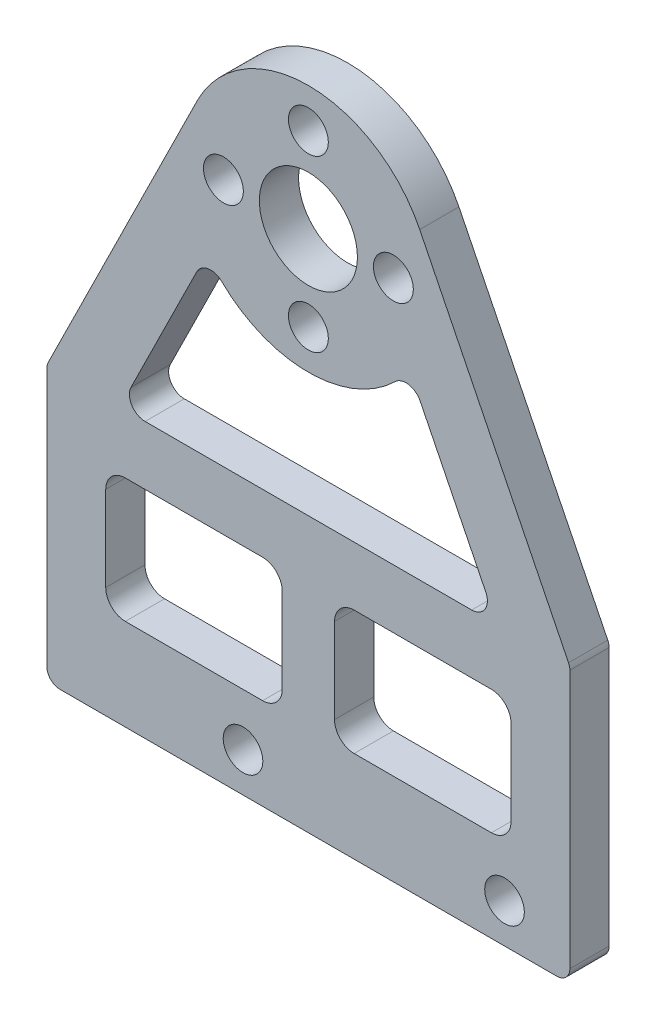
SolidWorks part; units mm, degrees
material "Thornel Mat VMA"
ref_plane "前视基准面" through (0, 0, 0) normal (0, 0, 1) x (1, 0, 0)
ref_plane "上视基准面" through (0, 0, 0) normal (0, 1, 0) x (1, 0, 0)
ref_plane "右视基准面" through (0, 0, 0) normal (1, 0, 0) x (0, 0, -1)
sketch "草图1" plane through (0, 0, 0) normal (0, 0, 1) x (1, 0, 0)
  line L0 (0, 0) -> (0, -40) construction
  line L1 (-20, -40) -> (20, -40)
  line L2 (20, -40) -> (20, -19)
  line L3 (20, -19) -> (8.5148, 4.2129)
  line L4 (-20, -19) -> (-8.5148, 4.2129)
  line L5 (-20, -40) -> (-20, -19)
  circle A0 centre (0, 0) radius 6.5 construction
  circle A1 centre (0, 6.5) radius 1.525
  circle A2 centre (6.5, 0) radius 1.525
  circle A3 centre (0, -6.5) radius 1.525
  circle A4 centre (-6.5, 0) radius 1.525
  circle A5 centre (0, 0) radius 3.75
  arc A6 (8.5148, 4.2129) -> (-8.5148, 4.2129) centre (0, 0) ccw
  point P14 (0, 0)
  point P18 (0, -40)
  dimension "D1" = 13
  dimension "D2" = 3.05
  dimension "D4" = 7.5
  dimension "D5" = 3
  dimension "D6" = 40
  dimension "D7" = 40
  dimension "D8" = 19
  dimension "D3" = 4
extrude "凸台-拉伸1" add sketch "草图1" along normal blind 3
fillet "圆角1" radius 1 4 edges at (-20, -40, 1.5) (-20, -19, 1.5) (20, -19, 1.5) (20, -40, 1.5)
sketch "草图2" plane through (0, 0, 0) normal (0, 0, -1) x (-1, 0, 0)
  circle A0 centre (5, -37) radius 1.25 construction
  circle A1 centre (-15, -37) radius 1.25 construction
  circle A2 centre (5, -37) radius 1.25 construction
  circle A3 centre (-15, -37) radius 1.25 construction
  circle A4 centre (-15, -37) radius 1.515
  circle A5 centre (5, -37) radius 1.515
  dimension "D1" = 3.03
extrude "切除-拉伸1" cut sketch "草图2" against normal blind 10
sketch "草图3" plane through (0, 0, 0) normal (0, 0, -1) x (-1, 0, 0)
  line L0 (-7.7436, -5.5033) -> (-14.4215, -19)
  line L1 (-14.4215, -19) -> (14.4215, -19)
  line L2 (14.4215, -19) -> (7.7436, -5.5033)
  line L3 (8.5148, 4.2129) -> (19.8963, -18.7904) construction
  line L4 (-19.8963, -18.7904) -> (-8.5148, 4.2129) construction
  arc A0 (-7.7436, -5.5033) -> (7.7436, -5.5033) centre (0, 0) ccw
  dimension "D1" = 19
  dimension "D3" = 5
  dimension "D4" = 5
  dimension "D2" = 19
extrude "切除-拉伸2" cut sketch "草图3" against normal blind 10
fillet "圆角2" radius 1.2 4 edges at (-7.7436, -5.5033, 1.5) (7.7436, -5.5033, 1.5) (-14.4215, -19, 1.5) (14.4215, -19, 1.5)
sketch "草图4" plane through (0, 0, 0) normal (0, 0, -1) x (-1, 0, 0)
  line L0 (-20, -39) -> (-20, -19.2339) construction
  line L1 (-15.5, -23.5) -> (15.5, -23.5)
  line L2 (-15.5, -23.5) -> (-15.5, -33)
  line L3 (-15.5, -33) -> (15.5, -33)
  line L4 (15.5, -23.5) -> (15.5, -33)
  line L5 (20, -19.2339) -> (20, -39) construction
  line L6 (-12.4889, -19) -> (12.4889, -19) construction
  circle A0 centre (5, -37) radius 1.515 construction
  dimension "D1" = 4.5
  dimension "D2" = 4.5
  dimension "D3" = 4
  dimension "D4" = 4.5
extrude "切除-拉伸3" cut sketch "草图4" against normal blind 10
sketch "草图5" plane through (0, 0, 0) normal (0, 0, -1) x (-1, 0, 0)
  line L0 (0, -23.5) -> (0, -33)
  line L1 (15.5, -23.5) -> (-15.5, -23.5) construction
  line L2 (-15.5, -33) -> (15.5, -33) construction
extrude "拉伸-薄壁1" add sketch "草图5" against normal blind 3 thin thin type mid plane wall 4
fillet "圆角3" radius 1.5 8 edges at (15.5, -23.5, 1.5) (2, -23.5, 1.5) (2, -33, 1.5) (15.5, -33, 1.5) (-15.5, -23.5, 1.5) (-15.5, -33, 1.5) (-2, -33, 1.5) (-2, -23.5, 1.5)
equation "\"D4@草图3\"=\"D3@草图3\""
